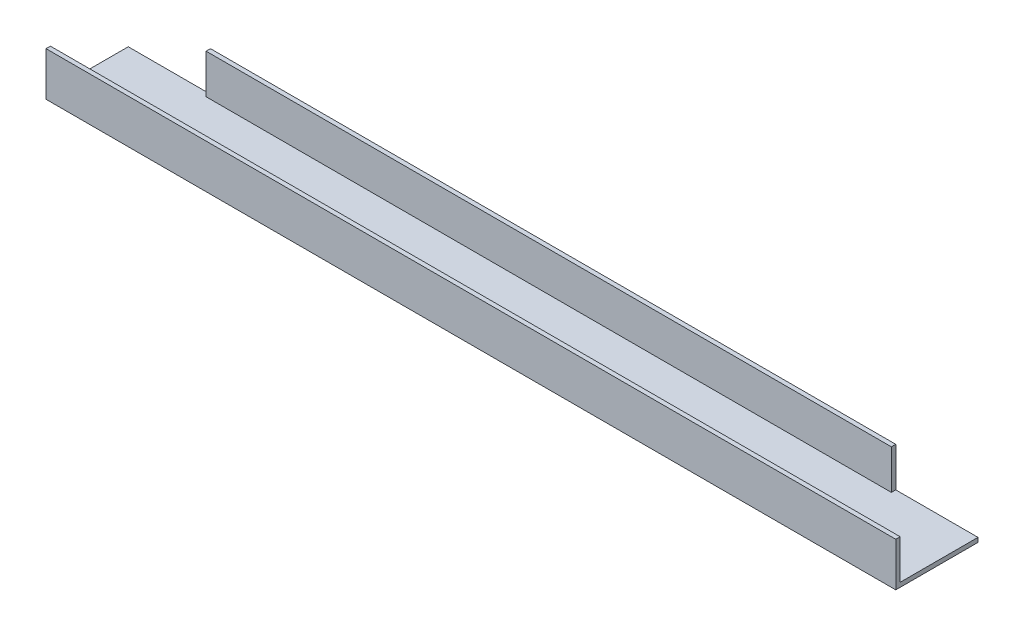
SolidWorks part; units mm, degrees
ref_plane "정면" through (0, 0, 0) normal (0, 0, 1) x (1, 0, 0)
ref_plane "윗면" through (0, 0, 0) normal (0, 1, 0) x (1, 0, 0)
ref_plane "우측면" through (0, 0, 0) normal (1, 0, 0) x (0, 0, -1)
sketch "스케치1" plane through (0, 0, 0) normal (0, 1, 0) x (1, 0, 0)
  line L1 (0, 0) -> (775, 0)
  line L2 (0, 0) -> (0, 75)
  line L3 (0, 75) -> (775, 75)
  line L4 (775, 0) -> (775, 75)
  dimension "D1" = 775
  dimension "D2" = 75
extrude "보스-돌출1" add sketch "스케치1" along normal blind 4
sketch "스케치2" plane through (0, 4, 0) normal (0, 1, 0) x (1, 0, 0)
  line L0 (775, 0) -> (775, 75) construction
  line L1 (0, 0) -> (775, 0)
  line L2 (0, 0) -> (0, 4)
  line L3 (0, 4) -> (775, 4)
  line L4 (775, 0) -> (775, 4)
  line L5 (775, 75) -> (0, 75) construction
  line L6 (700, 75) -> (75, 75)
  line L7 (700, 75) -> (700, 71)
  line L8 (700, 71) -> (75, 71)
  line L9 (75, 75) -> (75, 71)
  line L10 (0, 75) -> (0, 0) construction
  dimension "D1" = 4
  dimension "D2" = 4
  dimension "D3" = 75
  dimension "D4" = 625
extrude "보스-돌출2" add sketch "스케치2" along normal blind 36
